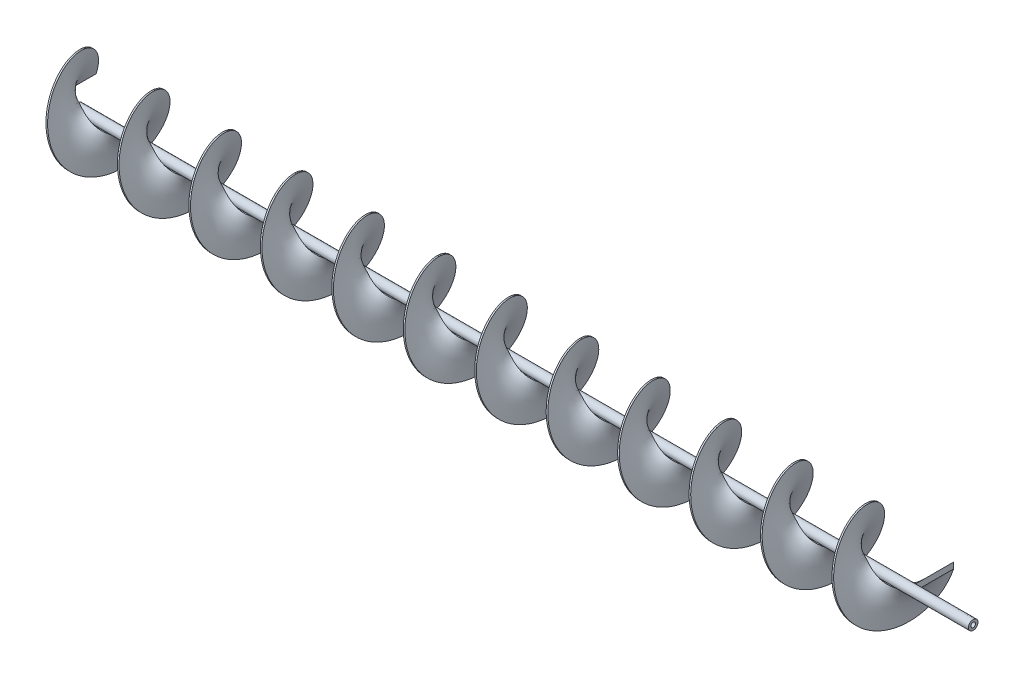
SolidWorks part; units mm, degrees
ref_plane "Vorderansicht" through (0, 0, 0) normal (0, 0, 1) x (1, 0, 0)
ref_plane "Draufsicht" through (0, 0, 0) normal (0, 1, 0) x (1, 0, 0)
ref_plane "Seitenansicht" through (0, 0, 0) normal (1, 0, 0) x (0, 0, -1)
sketch "Skizze3" plane through (0, 0, 0) normal (1, 0, 0) x (0, 0, -1)
  circle A0 centre (0, 0) radius 4
  circle A1 centre (0, 0) radius 2
  dimension "D1" = 8
  dimension "D2" = 2
extrude "Aufsatz-Linear austragen1" add sketch "Skizze3" against normal blind 700 and the other way blind 51.5 separate body
sketch "Skizze1" plane through (0, 0, 0) normal (1, 0, 0) x (0, 0, -1)
  circle A0 centre (0, 0) radius 4
  dimension "D1" = 8
curve "Spirale/Helix1" pitch 60 height 720 turns 12
sketch "Skizze2" plane through (0, 0, 0) normal (1, 0, 0) x (0, 0, -1)
  line L0 (19.3938, 0) -> (56.2084, 0) construction
  line L2 (4, -2.5) -> (35, -2.5)
  line L3 (4, -2.5) -> (4, 2.5)
  line L4 (4, 2.5) -> (35, 2.5)
  line L5 (35, -2.5) -> (35, 2.5)
  dimension "D1" = 35
  dimension "D2" = 4
  dimension "D3" = 5
sweep "Austragung1" add profiles "Skizze2" path "Spirale/Helix1"
